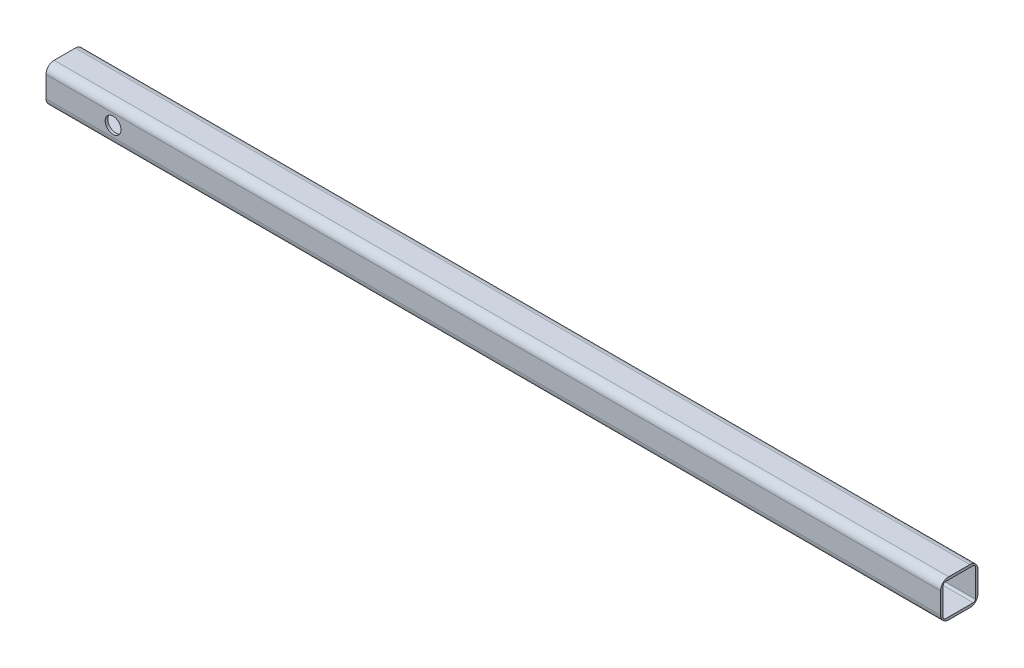
SolidWorks part; units mm, degrees
material "Thornel Mat VMA"
ref_plane "Front Plane" through (0, 0, 0) normal (0, 0, 1) x (1, 0, 0)
ref_plane "Top Plane" through (0, 0, 0) normal (0, 1, 0) x (1, 0, 0)
ref_plane "Right Plane" through (0, 0, 0) normal (1, 0, 0) x (0, 0, -1)
sketch "Sketch2" plane through (0, 0, 0) normal (1, 0, 0) x (0, 0, -1)
  line L1 (5.08, 0) -> (18.288, 0)
  line L2 (0, 5.08) -> (0, 18.288)
  line L3 (5.08, 23.368) -> (18.288, 23.368)
  line L4 (23.368, 5.08) -> (23.368, 18.288)
  line L5 (2.921, 1.651) -> (20.447, 1.651)
  line L6 (1.651, 2.921) -> (1.651, 20.447)
  line L7 (2.921, 21.717) -> (20.447, 21.717)
  line L8 (21.717, 2.921) -> (21.717, 20.447)
  arc A8 (5.08, 23.368) -> (0, 18.288) centre (5.08, 18.288) ccw
  arc A9 (18.288, 0) -> (23.368, 5.08) centre (18.288, 5.08) ccw
  arc A10 (18.288, 23.368) -> (23.368, 18.288) centre (18.288, 18.288) cw
  arc A11 (0, 5.08) -> (5.08, 0) centre (5.08, 5.08) ccw
  arc A12 (2.921, 21.717) -> (1.651, 20.447) centre (2.921, 20.447) ccw
  arc A13 (20.447, 21.717) -> (21.717, 20.447) centre (20.447, 20.447) cw
  arc A14 (20.447, 1.651) -> (21.717, 2.921) centre (20.447, 2.921) ccw
  arc A15 (2.921, 1.651) -> (1.651, 2.921) centre (2.921, 2.921) cw
  point P0 (0, 0)
  point P6 (23.368, 0)
  point P11 (23.368, 23.368)
  point P25 (21.717, 21.717)
  dimension "D7" = 5.08
  dimension "D5" = 1.651
  dimension "D2" = 5.08
  dimension "D18" = 5.08
  dimension "D12" = 1.27
  dimension "D13" = 1.27
  dimension "D11" = 1.27
  dimension "D14" = 1.27
  dimension "D3" = 20.066
  dimension "D4" = 20.066
  dimension "D6" = 1.651
  dimension "D8" = 23.368
  dimension "D9" = 23.368
  dimension "D10" = 23.368
extrude "Boss-Extrude1" add sketch "Sketch2" along normal blind 558.8
sketch "Sketch3" plane through (0, 0, 0) normal (0, 0, 1) x (1, 0, 0)
  line L0 (0, 18.288) -> (0, 5.08) construction
  line L2 (558.8, 23.368) -> (0, 23.368) construction
  circle A0 centre (41.91, 11.684) radius 4.953
  dimension "D1" = 9.906
  dimension "D2" = 41.91
  dimension "D3" = 11.684
extrude "Cut-Extrude1" cut sketch "Sketch3" against normal up to surface (23.368 mm away) up to face at (279.4, 11.684, -23.368)
sketch "Sketch4" plane through (558.8, 0, 0) normal (1, 0, 0) x (0, 0, -1)
  line L1 (0, 16.637) -> (0, 6.731)
  line L2 (0, 16.637) -> (0, 6.731)
  line L6 (23.368, 5.08) -> (23.368, 18.288)
  line L7 (5.08, 0) -> (18.288, 0)
  line L8 (0, 18.288) -> (0, 5.08)
  line L9 (18.288, 23.368) -> (5.08, 23.368)
  line L10 (23.368, 5.08) -> (23.368, 18.288)
  line L11 (5.08, 0) -> (18.288, 0)
  line L12 (0, 18.288) -> (0, 5.08)
  line L13 (18.288, 23.368) -> (5.08, 23.368)
  arc A4 (5.08, 23.368) -> (0, 18.288) centre (5.08, 18.288) ccw
  arc A5 (5.08, 23.368) -> (0, 18.288) centre (5.08, 18.288) ccw
  arc A6 (23.368, 18.288) -> (18.288, 23.368) centre (18.288, 18.288) ccw
  arc A7 (23.368, 18.288) -> (18.288, 23.368) centre (18.288, 18.288) ccw
  arc A12 (18.288, 0) -> (23.368, 5.08) centre (18.288, 5.08) ccw
  arc A13 (18.288, 0) -> (23.368, 5.08) centre (18.288, 5.08) ccw
  arc A14 (0, 5.08) -> (5.08, 0) centre (5.08, 5.08) ccw
  arc A15 (0, 5.08) -> (5.08, 0) centre (5.08, 5.08) ccw
  dimension "D1" = 0
  dimension "D2" = 0
equation "\"shaft\"=0.92"
equation "\"IDshaft\"=0.4375"
equation "\"D3@Sketch3\"=0.92/2"
